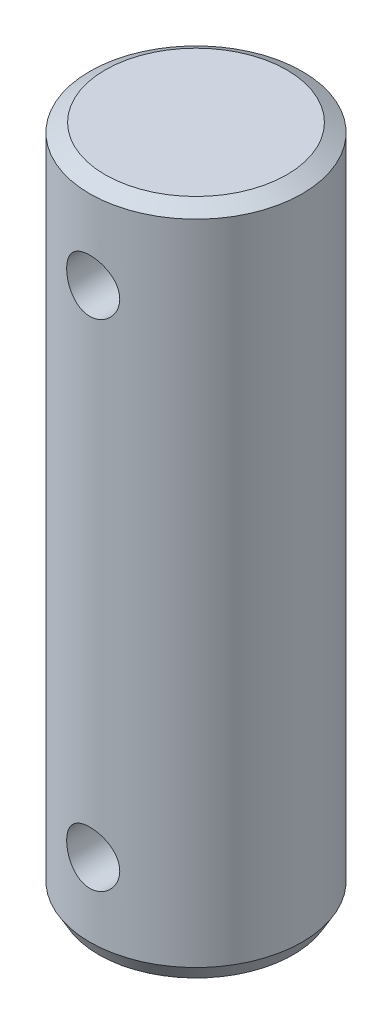
SolidWorks part; units mm, degrees
ref_plane "Front Plane" through (0, 0, 0) normal (0, 0, 1) x (1, 0, 0)
ref_plane "Top Plane" through (0, 0, 0) normal (0, 1, 0) x (1, 0, 0)
ref_plane "Right Plane" through (0, 0, 0) normal (1, 0, 0) x (0, 0, -1)
sketch "Sketch1" plane through (0, 0, 0) normal (0, 1, 0) x (1, 0, 0)
  circle A0 centre (0, 0) radius 6
  dimension "D1" = 12
extrude "Boss-Extrude1" add sketch "Sketch1" along normal mid plane 38
chamfer "Chamfer1" distance 0.5 angle 60 2 edges at (0, -19, 6) (0, 19, 6)
sketch "Sketch2" plane through (0, 0, 0) normal (0, 0, 1) x (1, 0, 0)
  line L1 (5.134, 19) -> (-5.134, 19) construction
  line L2 (-5.5, -19) -> (5.5, -19) construction
  circle A0 centre (0, 14) radius 1.5
  circle A1 centre (0, -14) radius 1.5
  point P8 (0, 0)
  point P9 (0, 0)
  dimension "D1" = 3
  dimension "D3" = 3
  dimension "D2" = 5
  dimension "D4" = 5
extrude "Cut-Extrude1" cut sketch "Sketch2" against normal mid plane 38
